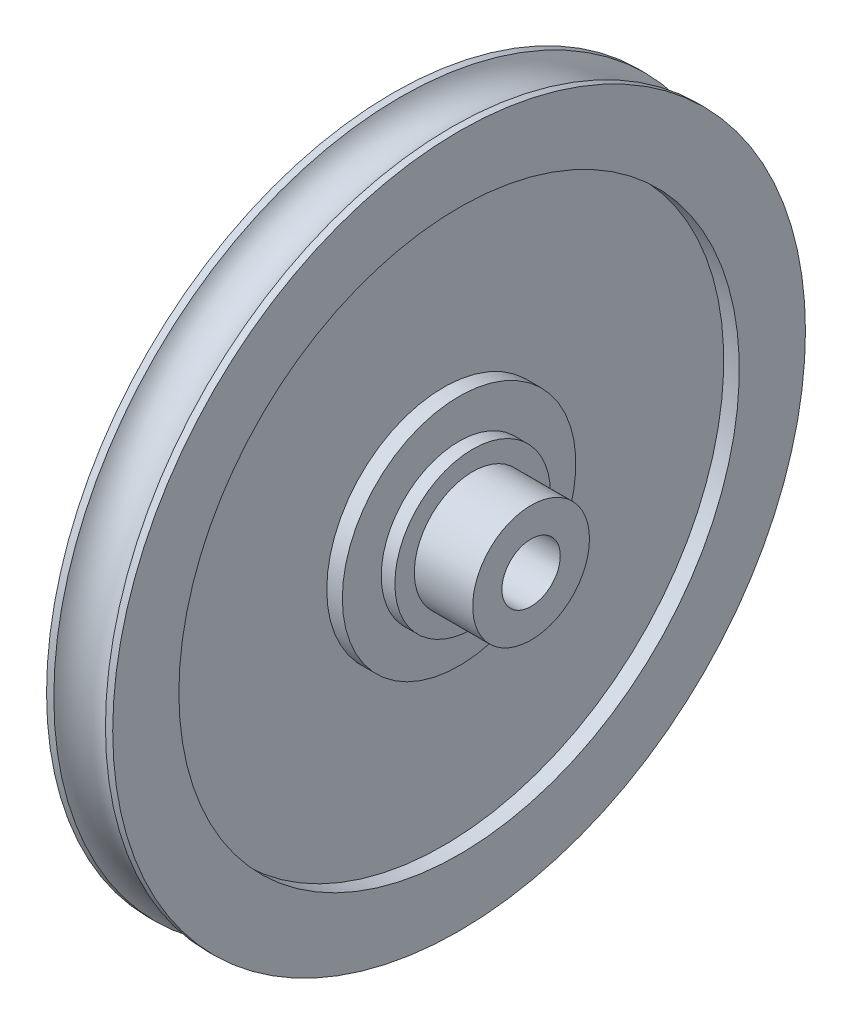
SolidWorks part; units mm, degrees
material "Alliage 1060"
ref_plane "Plan de face" through (0, 0, 0) normal (0, 0, 1) x (1, 0, 0)
ref_plane "Plan de dessus" through (0, 0, 0) normal (0, 1, 0) x (1, 0, 0)
ref_plane "Plan de droite" through (0, 0, 0) normal (1, 0, 0) x (0, 0, -1)
sketch "Esquisse2" plane through (0, 0, 0) normal (0, 0, 1) x (1, 0, 0)
  line L0 (0, 0) -> (0, 18.5) construction
  line L1 (-1.5, 18.5) -> (-1.7, 18.5)
  line L2 (-1.7, 18.5) -> (-1.7, 0)
  line L3 (-1.7, 0) -> (1.7, 0)
  line L4 (1.7, 0) -> (1.7, 6)
  line L5 (1.7, 18.5) -> (1.5, 18.5)
  line L6 (1.7, 17) -> (-1.7, 17) construction
  line L8 (-1.7, 20) -> (1.7, 20) construction
  line L9 (1.7, 14.4) -> (1.7, 18.5)
  line L10 (1.7, 6) -> (0.9, 6)
  line L11 (0.9, 14.4) -> (1.7, 14.4)
  line L12 (0.9, 6) -> (0.9, 14.4)
  arc A0 (1.5, 18.5) -> (-1.5, 18.5) centre (0, 18.5) cw
  arc A2 (1.5, 18.5) -> (-1.5, 18.5) centre (0, 18.5) ccw construction
  dimension "D1" = 1.5
  dimension "D2" = 3.4
  dimension "D3" = 17
  dimension "D4" = 6
  dimension "D6" = 14.4
  dimension "D7" = 0.8
revolve "Révolution1" add sketch "Esquisse2" angle 360 about L3
sketch "Esquisse4" plane through (0, 0, 0) normal (1, 0, 0) x (0, 0, -1)
  circle A0 centre (0, 0) radius 3
  dimension "D1" = 6
extrude "axe" add sketch "Esquisse4" along normal blind 5.4 and the other way blind 5.4
sketch "Esquisse6" plane through (1.7, 0, 0) normal (1, 0, 0) x (0, 0, -1)
  circle A0 centre (0, 0) radius 4
  dimension "D1" = 8
extrude "empaulement_roulement" add sketch "Esquisse6" along normal blind 0.7 contours A0
mirror "Symétrie1" about plane through (0, 0, 0) normal (1, 0, 0) of "empaulement_roulement"
sketch "Esquisse5" plane through (0, 0, 0) normal (1, 0, 0) x (0, 0, -1)
  circle A0 centre (0, 0) radius 1.5
  dimension "D1" = 3
extrude "axe_3mm" cut sketch "Esquisse5" against normal through all and the other way through all
sketch "Esquisse7" plane through (0, 0, 0) normal (0, 0, 1) x (1, 0, 0)
  line L0 (0, 0) -> (0, 18.15) construction
  line L1 (0, 0) -> (7.738, 0) construction
  line L2 (-2.4821, 17.8) -> (2.4821, 17.8)
  line L3 (-2.4821, 17.8) -> (-2.4821, 18.5)
  line L4 (-2.4821, 18.5) -> (2.4821, 18.5)
  line L5 (2.4821, 17.8) -> (2.4821, 18.5)
  line L6 (-2.4821, 17.8) -> (2.4821, 18.5) construction
  line L7 (-2.4821, 18.5) -> (2.4821, 17.8) construction
  dimension "D1" = 0.7
revolve "Enlèvement de matière-Révolution1" cut sketch "Esquisse7" angle 360 about L1
